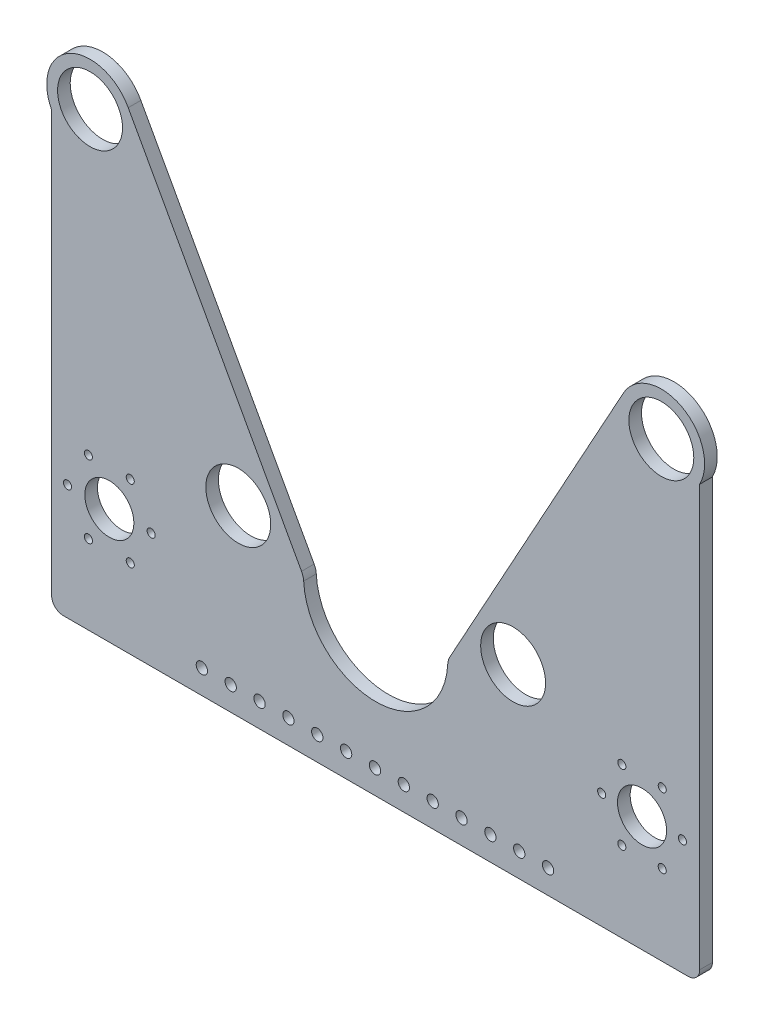
SolidWorks part; units mm, degrees
ref_plane "Front Plane" through (0, 0, 0) normal (0, 0, 1) x (1, 0, 0)
ref_plane "Top Plane" through (0, 0, 0) normal (0, 1, 0) x (1, 0, 0)
ref_plane "Right Plane" through (0, 0, 0) normal (1, 0, 0) x (0, 0, -1)
sketch "Sketch2" plane through (0, 0, 0) normal (0, 0, 1) x (1, 0, 0)
  line L0 (-106.68, -1064.2295) -> (-106.68, 48935.7705) construction
  line L1 (142.6324, 122.4629) -> (142.6324, -29.9371)
  line L2 (106.68, -1098.4025) -> (106.68, 48901.5975) construction
  line L3 (31.75, 0) -> (108.9183, 140.209)
  line L4 (0, -1082.0685) -> (0, 48917.9315) construction
  line L5 (-106.68, -44.45) -> (106.68, -44.45) construction
  line L7 (0, -31.75) -> (106.68, -31.75) construction
  line L8 (106.68, -55.9582) -> (106.68, -31.75)
  line L9 (-31.75, 0) -> (-108.9183, 140.209)
  line L10 (31.75, 0) -> (108.9183, 140.209)
  line L22 (-142.6324, -56.7419) -> (-142.6324, -62.6205)
  line L33 (-106.5644, -31.75) -> (0, -31.75) construction
  line L34 (-142.6324, 122.4629) -> (-142.6324, -29.9371)
  line L36 (-261.1394, 46.2048) -> (-243.4617, 46.2048) construction
  line L37 (-243.4617, 46.2048) -> (-243.4617, 28.5272) construction
  line L41 (-238.3305, 62.766) -> (-266.2705, 62.766) construction
  line L42 (-233.2505, 57.686) -> (-233.2505, 17.046) construction
  line L43 (-261.1394, 46.2048) -> (-261.1394, 28.5272) construction
  line L44 (-261.1394, 28.5272) -> (-243.4617, 28.5272) construction
  line L45 (-238.3305, 11.966) -> (-266.2705, 11.966) construction
  line L46 (-271.3505, 57.686) -> (-271.3505, 17.046) construction
  line L47 (-233.2505, 62.766) -> (-271.3505, 11.966) construction
  line L48 (-125.73, 3.175) -> (-125.73, -22.225) construction
  line L49 (-1101.9372, -9.525) -> (48898.0628, -9.525) construction
  line L50 (-233.2505, 11.966) -> (-271.3505, 62.766) construction
  line L51 (-239.6005, 56.416) -> (-239.6005, 18.316) construction
  line L52 (-265.0005, 56.416) -> (-239.6005, 56.416) construction
  line L53 (-125.73, 3.175) -> (-106.68, 3.175) construction
  line L54 (-142.6324, -56.7419) -> (142.6324, -56.7419) construction
  line L55 (-142.6324, -29.9371) -> (-142.6324, -56.7419)
  line L56 (142.6324, -29.9371) -> (142.6324, -56.7419)
  line L57 (-137.5524, -67.7005) -> (137.5524, -67.7005)
  line L58 (142.6324, -62.6205) -> (142.6324, -56.7419)
  arc A0 (-31.75, 0) -> (31.75, 0) centre (0, 0) ccw
  arc A1 (-108.9183, 140.209) -> (-142.6324, 122.4629) centre (-125.7268, 131.2438) ccw
  circle A2 centre (-60.4845, 12.7) radius 14.2875
  arc A3 (31.75, 0) -> (0, 31.75) centre (0, 0) ccw construction
  arc A4 (0, 31.75) -> (-31.75, 0) centre (0, 0) ccw construction
  arc A5 (137.5524, -67.7005) -> (142.6324, -62.6205) centre (137.5524, -62.6205) ccw
  arc A6 (-142.6324, -62.6205) -> (-137.5524, -67.7005) centre (-137.5524, -62.6205) ccw
  circle A7 centre (-125.7268, 131.2438) radius 14.2875
  circle A9 centre (-60.4845, 12.7) radius 19.05 construction
  circle A10 centre (60.4845, 12.7) radius 19.05 construction
  arc A11 (108.9183, 140.209) -> (142.6324, 122.4629) centre (125.7268, 131.2438) cw
  circle A12 centre (125.7268, 131.2438) radius 14.2875
  arc A40 (-142.6324, 122.4629) -> (-108.9183, 140.209) centre (-125.7268, 131.2438) ccw construction
  arc A41 (142.6324, 122.4629) -> (108.9183, 140.209) centre (125.7268, 131.2438) cw construction
  circle A42 centre (60.4845, 12.7) radius 14.2875
  circle A44 centre (-76.5175, -57.15) radius 2.4892
  circle A45 centre (-63.8175, -57.15) radius 2.4892
  circle A46 centre (-51.1175, -57.15) radius 2.4892
  circle A47 centre (-38.4175, -57.15) radius 2.4892
  circle A48 centre (-25.7175, -57.15) radius 2.4892
  circle A49 centre (-13.0175, -57.15) radius 2.4892
  circle A50 centre (-0.3175, -57.15) radius 2.4892
  circle A51 centre (12.3825, -57.15) radius 2.4892
  circle A52 centre (25.0825, -57.15) radius 2.4892
  circle A53 centre (37.7825, -57.15) radius 2.4892
  circle A54 centre (50.4825, -57.15) radius 2.4892
  circle A55 centre (63.1825, -57.15) radius 2.4892
  circle A56 centre (75.8825, -57.15) radius 2.4892
  arc A100 (-260.1552, 27.7564) -> (-262.1235, 29.2979) centre (-261.1394, 28.5272) ccw construction
  arc A101 (-262.1235, 29.2979) -> (-260.1552, 27.7564) centre (-261.1394, 28.5272) ccw construction
  arc A102 (-244.4458, 29.2979) -> (-242.4776, 27.7564) centre (-243.4617, 28.5272) ccw construction
  arc A103 (-242.4776, 27.7564) -> (-244.4458, 29.2979) centre (-243.4617, 28.5272) ccw construction
  arc A104 (-242.4776, 45.4341) -> (-244.4458, 46.9756) centre (-243.4617, 46.2048) ccw construction
  arc A105 (-244.4458, 46.9756) -> (-242.4776, 45.4341) centre (-243.4617, 46.2048) ccw construction
  arc A106 (-262.1235, 46.9756) -> (-260.1552, 45.4341) centre (-261.1394, 46.2048) ccw construction
  arc A107 (-260.1552, 45.4341) -> (-262.1235, 46.9756) centre (-261.1394, 46.2048) ccw construction
  circle A108 centre (-252.3005, 37.366) radius 7.3172 construction
  circle A109 centre (-265.0005, 56.416) radius 3.175 construction
  circle A110 centre (-239.6005, 56.416) radius 3.175 construction
  circle A111 centre (-239.6005, 18.316) radius 3.175 construction
  circle A112 centre (-265.0005, 18.316) radius 3.175 construction
  arc A113 (-266.2705, 11.966) -> (-271.3505, 17.046) centre (-266.2705, 17.046) cw construction
  arc A114 (-233.2505, 17.046) -> (-238.3305, 11.966) centre (-238.3305, 17.046) cw construction
  arc A115 (-238.3305, 62.766) -> (-233.2505, 57.686) centre (-238.3305, 57.686) cw construction
  arc A116 (-266.2705, 62.766) -> (-271.3505, 57.686) centre (-266.2705, 57.686) ccw construction
  circle A134 centre (-117.2324, -16.9005) radius 10.795
  circle A135 centre (117.2324, -16.9005) radius 10.795
  circle A137 centre (-135.6474, -16.9005) radius 1.778
  circle A141 centre (-126.4399, -0.9526) radius 1.778
  circle A142 centre (-108.0249, -0.9526) radius 1.778
  circle A143 centre (-98.8174, -16.9005) radius 1.778
  circle A144 centre (-108.0249, -32.8484) radius 1.778
  circle A145 centre (-126.4399, -32.8484) radius 1.778
  circle A147 centre (99.4524, -16.9005) radius 1.778
  circle A148 centre (108.3424, -1.5026) radius 1.778
  circle A149 centre (126.1224, -1.5026) radius 1.778
  circle A150 centre (135.0124, -16.9005) radius 1.778
  circle A151 centre (126.1224, -32.2984) radius 1.778
  circle A152 centre (108.3424, -32.2984) radius 1.778
  point P81 (-117.2324, -16.9005)
  point P83 (106.68, -30.0086)
  point P96 (117.2324, -16.9005)
  point P97 (-106.68, -29.6005)
  point P154 (-125.73, -9.525)
  dimension "D7" = 131.2438
  dimension "D8" = 25.4
  dimension "D9" = 50.8
  dimension "D3" = 44.45
  dimension "D14" = 106.68
  dimension "D17" = 38.1
  dimension "D5" = 5.08
  dimension "D15" = 31.75
  dimension "D16" = 28.575
  dimension "D18" = 28.575
  dimension "D19" = 19.05
  dimension "D23" = 4.9784
  dimension "D24" = 3.556
  dimension "D21" = 125.7268
  dimension "D33" = 6.35
  dimension "D35" = 8.8388
  dimension "D37" = 8.8388
  dimension "D42" = 36.068
  dimension "D34" = 6.35
  dimension "D36" = 1.25
  dimension "D38" = 5.08
  dimension "D11" = 25.4
  dimension "D12" = 50.8
  dimension "D13" = 6
  dimension "D22" = 6
  dimension "D1" = 28.828
  dimension "D6" = 10.9586
  dimension "D10" = 35.9524
  dimension "D20" = 142.6324
  dimension "D25" = 152.4
  dimension "D26" = 12.7
  dimension "D32" = 6.35
  dimension "D29" = 17.6777
  dimension "D30" = 50.8
  dimension "D31" = 38.1
  dimension "D39" = 25.4
  dimension "D40" = 38.1
  dimension "D41" = 16.9024
extrude "Boss-Extrude1" add sketch "Sketch2" along normal blind 3.175
sketch "Sketch3" plane through (0, 0, 3.175) normal (0, 0, -1) x (-1, 0, 0)
  line L0 (-125.7268, 150.2938) -> (49874.2732, 150.2938) construction
  line L1 (-144.7768, 131.2438) -> (-144.7768, 50131.2438) construction
  point P4 (-144.7768, 150.2938)
fillet "Fillet1" radius 7.62 2 edges at (31.75, 0, 1.5875) (-31.75, 0, 1.5875)
sketch "Sketch4" plane through (0, 0, 0) normal (0, 0, -1) x (-1, 0, 0)
  line L5 (-32.6406, 1.6181) -> (-108.9183, 140.209)
  line L6 (-142.6324, 122.4629) -> (-142.6324, -62.6205)
  line L7 (-137.5524, -67.7005) -> (137.5524, -67.7005)
  line L8 (142.6324, -62.6205) -> (142.6324, 122.4629)
  line L9 (108.9183, 140.209) -> (32.6406, 1.6181)
  line L10 (-32.6406, 1.6181) -> (-108.9183, 140.209)
  line L11 (-142.6324, 122.4629) -> (-142.6324, -62.6205)
  line L12 (-137.5524, -67.7005) -> (137.5524, -67.7005)
  line L13 (142.6324, -62.6205) -> (142.6324, 122.4629)
  line L14 (108.9183, 140.209) -> (32.6406, 1.6181)
  circle A0 centre (125.7268, 131.2438) radius 14.2875 construction
  circle A1 centre (108.0249, -32.8484) radius 1.778 construction
  circle A2 centre (126.4399, -32.8484) radius 1.778 construction
  circle A3 centre (135.6474, -16.9005) radius 1.778 construction
  circle A4 centre (126.4399, -0.9526) radius 1.778 construction
  circle A5 centre (108.0249, -0.9526) radius 1.778 construction
  circle A6 centre (98.8174, -16.9005) radius 1.778 construction
  arc A7 (-31.7067, -1.6581) -> (31.7067, -1.6581) centre (0, 0) ccw
  arc A8 (-31.7067, -1.6581) -> (-32.6406, 1.6181) centre (-39.3163, -2.056) ccw
  arc A9 (-108.9183, 140.209) -> (-142.6324, 122.4629) centre (-125.7268, 131.2438) ccw
  arc A10 (-142.6324, -62.6205) -> (-137.5524, -67.7005) centre (-137.5524, -62.6205) ccw
  arc A11 (137.5524, -67.7005) -> (142.6324, -62.6205) centre (137.5524, -62.6205) ccw
  arc A12 (142.6324, 122.4629) -> (108.9183, 140.209) centre (125.7268, 131.2438) ccw
  arc A13 (32.6406, 1.6181) -> (31.7067, -1.6581) centre (39.3163, -2.056) ccw
  arc A14 (-31.7067, -1.6581) -> (31.7067, -1.6581) centre (0, 0) ccw
  arc A15 (-31.7067, -1.6581) -> (-32.6406, 1.6181) centre (-39.3163, -2.056) ccw
  arc A16 (-108.9183, 140.209) -> (-142.6324, 122.4629) centre (-125.7268, 131.2438) ccw
  arc A17 (-142.6324, -62.6205) -> (-137.5524, -67.7005) centre (-137.5524, -62.6205) ccw
  arc A18 (137.5524, -67.7005) -> (142.6324, -62.6205) centre (137.5524, -62.6205) ccw
  arc A19 (142.6324, 122.4629) -> (108.9183, 140.209) centre (125.7268, 131.2438) ccw
  arc A20 (32.6406, 1.6181) -> (31.7067, -1.6581) centre (39.3163, -2.056) ccw
  circle A21 centre (117.2324, -16.9005) radius 10.795 construction
  circle A22 centre (60.4845, 12.7) radius 14.2875 construction
  circle A23 centre (76.5175, -57.15) radius 2.4892 construction
  circle A24 centre (63.8175, -57.15) radius 2.4892 construction
  circle A25 centre (51.1175, -57.15) radius 2.4892 construction
  circle A26 centre (38.4175, -57.15) radius 2.4892 construction
  circle A27 centre (25.7175, -57.15) radius 2.4892 construction
  circle A28 centre (13.0175, -57.15) radius 2.4892 construction
  circle A29 centre (0.3175, -57.15) radius 2.4892 construction
  circle A30 centre (-12.3825, -57.15) radius 2.4892 construction
  circle A31 centre (-25.0825, -57.15) radius 2.4892 construction
  circle A32 centre (-37.7825, -57.15) radius 2.4892 construction
  circle A33 centre (-50.4825, -57.15) radius 2.4892 construction
  circle A34 centre (-63.1825, -57.15) radius 2.4892 construction
  circle A35 centre (-75.8825, -57.15) radius 2.4892 construction
  circle A36 centre (-99.4524, -16.9005) radius 1.778 construction
  circle A37 centre (-108.3424, -32.2984) radius 1.778 construction
  circle A38 centre (-126.1224, -32.2984) radius 1.778 construction
  circle A39 centre (-135.0124, -16.9005) radius 1.778 construction
  circle A40 centre (-126.1224, -1.5026) radius 1.778 construction
  circle A41 centre (-108.3424, -1.5026) radius 1.778 construction
  circle A42 centre (-117.2324, -16.9005) radius 10.795 construction
  circle A43 centre (-60.4845, 12.7) radius 14.2875 construction
  circle A44 centre (-125.7268, 131.2438) radius 14.2875 construction
  circle A45 centre (125.7268, 131.2438) radius 14.2875
  circle A46 centre (108.0249, -32.8484) radius 1.778
  circle A47 centre (126.4399, -32.8484) radius 1.778
  circle A48 centre (135.6474, -16.9005) radius 1.778
  circle A49 centre (126.4399, -0.9526) radius 1.778
  circle A50 centre (108.0249, -0.9526) radius 1.778
  circle A51 centre (98.8174, -16.9005) radius 1.778
  circle A52 centre (117.2324, -16.9005) radius 10.795
  circle A53 centre (60.4845, 12.7) radius 14.2875
  circle A54 centre (76.5175, -57.15) radius 2.4892
  circle A55 centre (63.8175, -57.15) radius 2.4892
  circle A56 centre (51.1175, -57.15) radius 2.4892
  circle A57 centre (38.4175, -57.15) radius 2.4892
  circle A58 centre (25.7175, -57.15) radius 2.4892
  circle A59 centre (13.0175, -57.15) radius 2.4892
  circle A60 centre (0.3175, -57.15) radius 2.4892
  circle A61 centre (-12.3825, -57.15) radius 2.4892
  circle A62 centre (-25.0825, -57.15) radius 2.4892
  circle A63 centre (-37.7825, -57.15) radius 2.4892
  circle A64 centre (-50.4825, -57.15) radius 2.4892
  circle A65 centre (-63.1825, -57.15) radius 2.4892
  circle A66 centre (-75.8825, -57.15) radius 2.4892
  circle A67 centre (-99.4524, -16.9005) radius 1.778
  circle A68 centre (-108.3424, -32.2984) radius 1.778
  circle A69 centre (-126.1224, -32.2984) radius 1.778
  circle A70 centre (-135.0124, -16.9005) radius 1.778
  circle A71 centre (-126.1224, -1.5026) radius 1.778
  circle A72 centre (-108.3424, -1.5026) radius 1.778
  circle A73 centre (-117.2324, -16.9005) radius 10.795
  circle A74 centre (-60.4845, 12.7) radius 14.2875
  circle A75 centre (-125.7268, 131.2438) radius 14.2875
  dimension "D1" = 0
extrude "Boss-Extrude2" add sketch "Sketch4" along normal blind 2.3813
